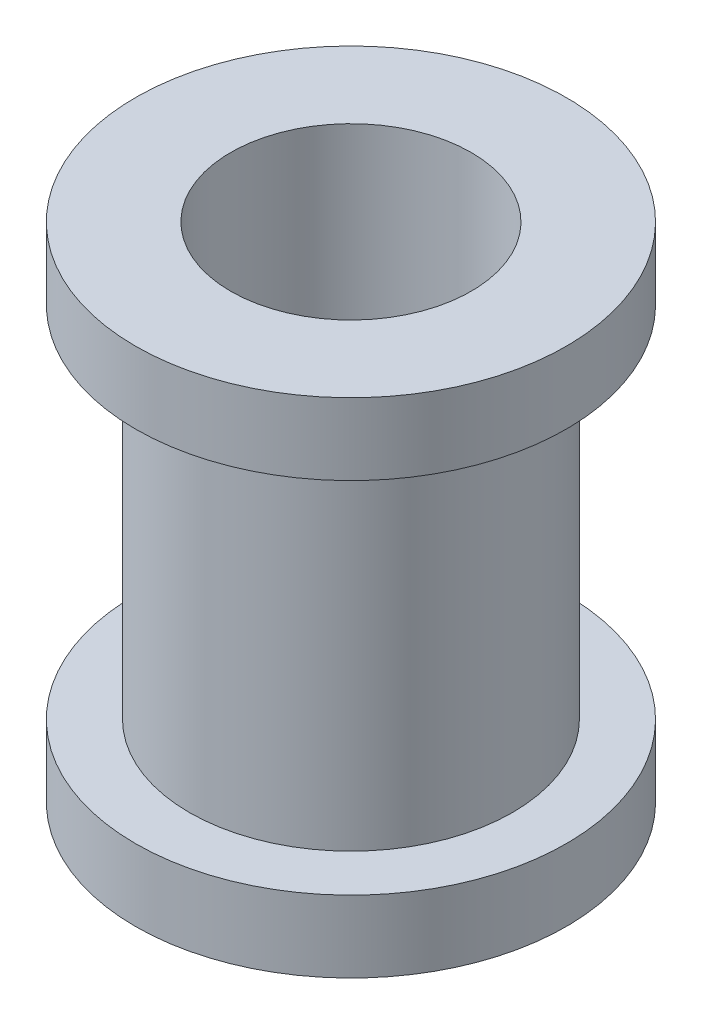
SolidWorks part; units mm, degrees
ref_plane "Front Plane" through (0, 0, 0) normal (0, 0, 1) x (1, 0, 0)
ref_plane "Top Plane" through (0, 0, 0) normal (0, 1, 0) x (1, 0, 0)
ref_plane "Right Plane" through (0, 0, 0) normal (1, 0, 0) x (0, 0, -1)
sketch "Sketch1" plane through (0, 0, 0) normal (0, 1, 0) x (1, 0, 0)
  circle A0 centre (0, 0) radius 4.5
  circle A1 centre (0, 0) radius 3.35
  dimension "D1" = 9
  dimension "D2" = 6.7
extrude "Boss-Extrude1" add sketch "Sketch1" along normal mid plane 10
sketch "Sketch2" plane through (0, 5, 0) normal (0, 1, 0) x (1, 0, 0)
  circle A0 centre (0, 0) radius 6
  circle A1 centre (0, 0) radius 3.35
  circle A2 centre (0, 0) radius 3.35 construction
  dimension "D1" = 12
extrude "Boss-Extrude2" add sketch "Sketch2" along normal blind 2
mirror "Mirror1" about plane through (0, 0, 0) normal (0, 1, 0) of "Boss-Extrude2"
